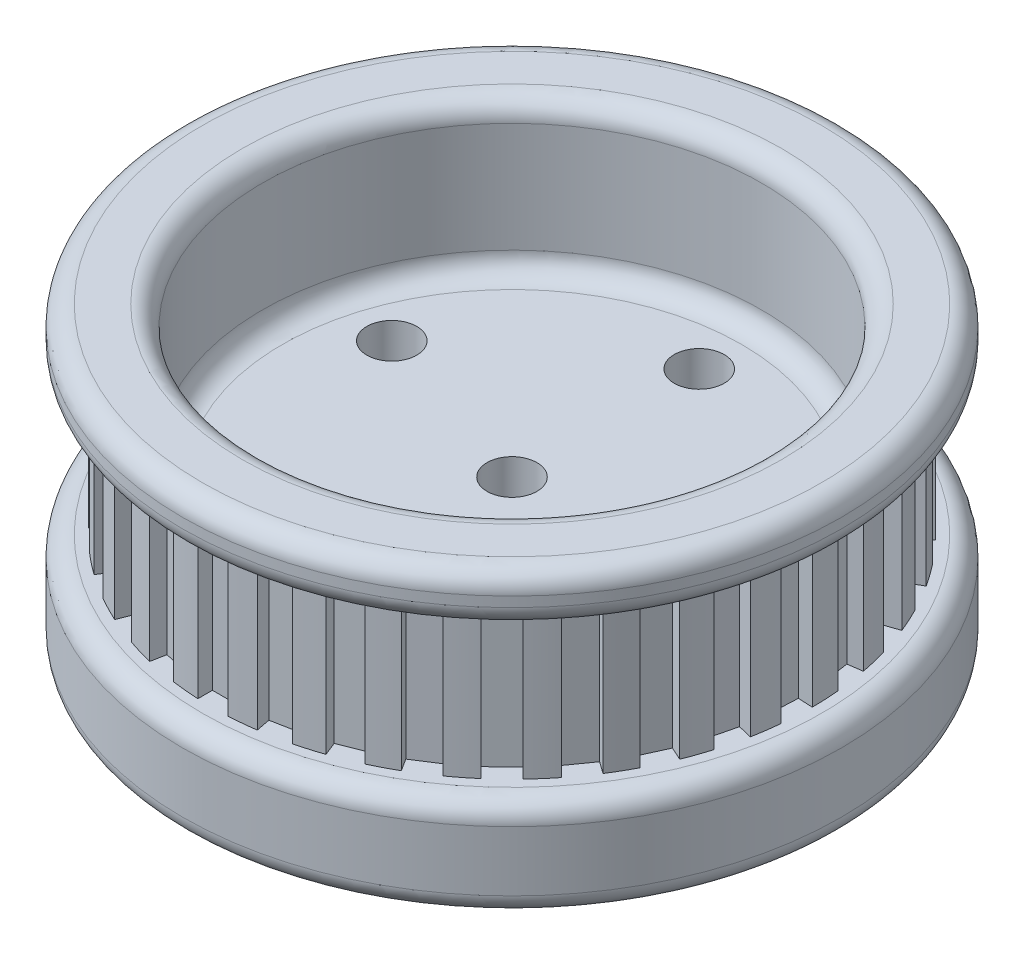
SolidWorks part; units mm, degrees
ref_plane "Front Plane" through (0, 0, 0) normal (0, 0, 1) x (1, 0, 0)
ref_plane "Top Plane" through (0, 0, 0) normal (0, 1, 0) x (1, 0, 0)
ref_plane "Right Plane" through (0, 0, 0) normal (1, 0, 0) x (0, 0, -1)
sketch "Sketch1" plane through (0, 0, 0) normal (0, 0, 1) x (1, 0, 0)
  line L0 (25, 10) -> (25, 25)
  line L1 (0, 0) -> (25, 0)
  line L2 (0, 0) -> (0, 10)
  line L3 (0, 10) -> (25, 10)
  line L5 (25, -5) -> (33, -5)
  line L6 (25, -5) -> (25, 0)
  line L7 (25, 25) -> (33, 25)
  line L8 (33, -5) -> (33, 5)
  line L9 (33, 5) -> (30, 5)
  line L11 (33, 20) -> (30, 20)
  line L12 (30, 5) -> (30, 20)
  line L13 (33, 20) -> (33, 25)
  dimension "D1" = 8
  dimension "D2" = 25
  dimension "D3" = 10
  dimension "D4" = 5
  dimension "D5" = 10
  dimension "D6" = 3
  dimension "D7" = 15
  dimension "D8" = 5
revolve "Revolve1" add sketch "Sketch1" angle 360 about L2
sketch "Sketch2" plane through (0, 10, 0) normal (0, 1, 0) x (1, 0, 0)
  circle A0 centre (0, 0) radius 2.5
  circle A1 centre (0, 0) radius 18.75 construction
  circle A2 centre (0, 18.75) radius 2.5
  circle A3 centre (17.8323, 5.7941) radius 2.5
  circle A4 centre (11.021, -15.1691) radius 2.5
  circle A5 centre (-11.021, -15.1691) radius 2.5
  circle A6 centre (-17.8323, 5.7941) radius 2.5
  point P17 (0, 0)
  dimension "D1" = 5
  dimension "D2" = 5
  dimension "D3" = 37.5
  dimension "D4" = 5
extrude "Cut-Extrude1" cut sketch "Sketch2" against normal blind 10
sketch "Sketch3" plane through (0, 5, 0) normal (0, 1, 0) x (1, 0, 0)
  line L0 (0, 0) -> (0, -30) construction
  line L2 (-1.5, -28.5) -> (1.5, -28.5)
  line L3 (-1.5, -28.5) -> (-1.5, -31.5)
  line L4 (-1.5, -31.5) -> (1.5, -31.5)
  line L5 (1.5, -28.5) -> (1.5, -31.5)
  line L6 (-1.5, -28.5) -> (1.5, -31.5) construction
  line L7 (-1.5, -31.5) -> (1.5, -28.5) construction
  circle A0 centre (0, 0) radius 30 construction
  dimension "D1" = 3
  dimension "D2" = 3
extrude "Cut-Extrude2" cut sketch "Sketch3" along normal up to surface (15 mm away) up to face at (0, 20, -33)
pattern_circular "CirPattern1" count 33 over 360 about axis through (0, 0, 0) along (0, 1, 0) of "Cut-Extrude2"
fillet "Fillet3" radius 2 8 edges at (0, -5, -25) (0, -5, -33) (0, 5, -33) (0, 20, -33) (0, 25, -33) (0, 25, -25) (0, 10, -25) (0, 0, -25)
